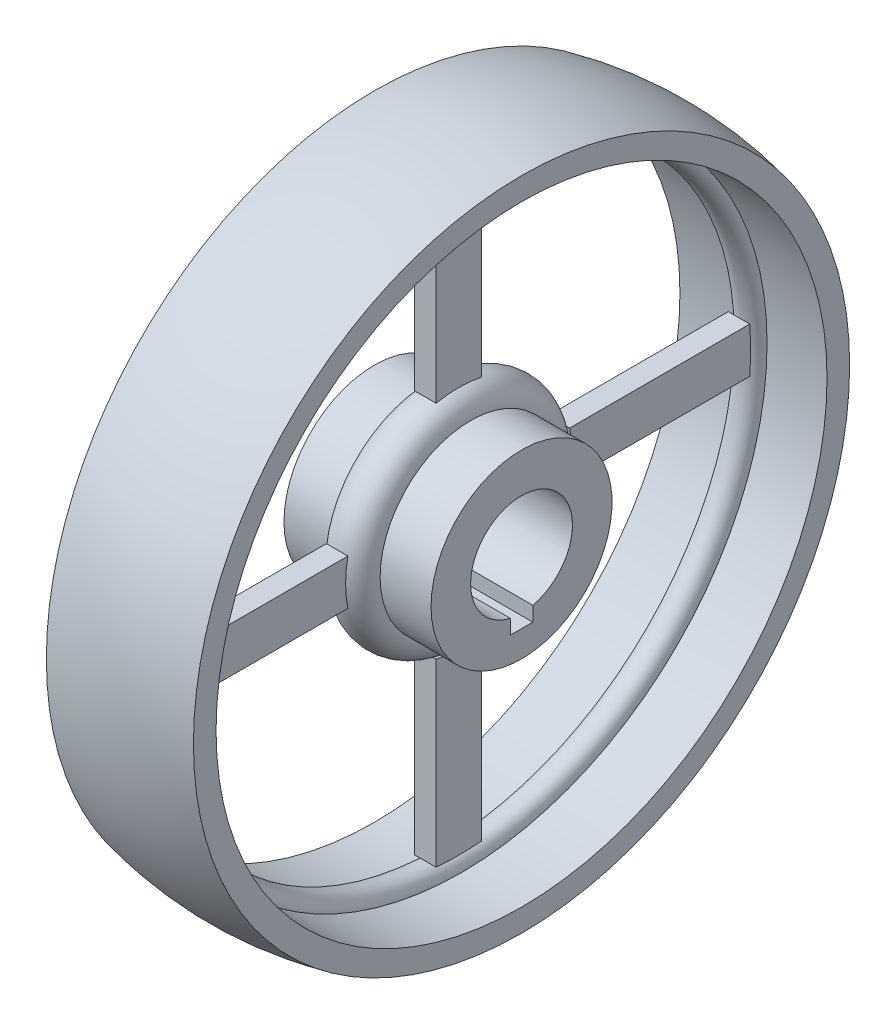
SolidWorks part; units mm, degrees
ref_plane "Front Plane" through (0, 0, 0) normal (0, 0, 1) x (1, 0, 0)
ref_plane "Top Plane" through (0, 0, 0) normal (0, 1, 0) x (1, 0, 0)
ref_plane "Right Plane" through (0, 0, 0) normal (1, 0, 0) x (0, 0, -1)
sketch "Sketch1" plane through (0, 0, 0) normal (0, 0, 1) x (1, 0, 0)
  line L0 (-46.3351, 0) -> (51.8981, 0) construction
  line L1 (-32.5, 10) -> (32.5, 10)
  line L2 (-32.5, 40) -> (-10, 40)
  line L5 (32.5, 10) -> (32.5, 40)
  line L6 (-32.5, 10) -> (-32.5, 40)
  line L7 (-32.5, 135) -> (-6, 135)
  line L8 (6, 135) -> (32.5, 135)
  line L9 (-32.5, 135) -> (-32.5, 145)
  line L11 (-46.3351, 135) -> (51.8981, 135) construction
  line L12 (32.5, 135) -> (32.5, 145)
  line L14 (10, 40) -> (32.5, 40)
  line L17 (-46.3351, 40) -> (51.8981, 40) construction
  line L18 (-46.3351, 10) -> (51.8981, 10) construction
  arc A0 (32.5, 145) -> (-32.5, 145) centre (0, 0) ccw
  arc A1 (-6, 135) -> (6, 135) centre (0, 135) ccw
  arc A2 (10, 40) -> (-10, 40) centre (0, 40) ccw
  point P7 (-46.3351, 50)
  point P8 (51.8981, 50)
  point P10 (0, 145)
  point P11 (32.5, 0)
  point P13 (-32.5, 0)
  dimension "D3" = 148.5976
  dimension "D4" = 6
  dimension "D5" = 10
  dimension "D6" = 32.5
  dimension "D7" = 135
  dimension "D1" = 10
  dimension "D2" = 40
revolve "Revolve1" add sketch "Sketch1" angle 360 about L0
sketch "Sketch2" plane through (0, 0, 0) normal (1, 0, 0) x (0, 0, -1)
  circle A0 centre (0, 0) radius 50
  circle A1 centre (0, 0) radius 129
extrude "Boss-Extrude1" add sketch "Sketch2" along normal mid plane 9.5 separate body
sketch "Sketch3" plane through (4.75, 0, 0) normal (1, 0, 0) x (0, 0, -1)
  line L1 (48.9898, 10) -> (128.6118, 10)
  line L2 (10, 48.9898) -> (10, 128.6118)
  line L4 (-10, 48.9898) -> (-10, 128.6118)
  line L5 (48.9898, -10) -> (128.6118, -10)
  line L6 (10, -48.9898) -> (10, -128.6118)
  line L7 (-10, -48.9898) -> (-10, -128.6118)
  line L8 (-48.9898, -10) -> (-128.6118, -10)
  line L9 (-48.9898, 10) -> (-128.6118, 10)
  arc A3 (-10, 128.6118) -> (-128.6118, 10) centre (0, 0) ccw
  arc A4 (-48.9898, -10) -> (-10, -48.9898) centre (0, 0) ccw
  arc A5 (128.6118, 10) -> (10, 128.6118) centre (0, 0) ccw
  arc A6 (-128.6118, -10) -> (-10, -128.6118) centre (0, 0) ccw
  arc A7 (10, -48.9898) -> (48.9898, -10) centre (0, 0) ccw
  arc A8 (-10, 48.9898) -> (-48.9898, 10) centre (0, 0) ccw
  arc A9 (48.9898, 10) -> (10, 48.9898) centre (0, 0) ccw
  arc A10 (10, -128.6118) -> (128.6118, -10) centre (0, 0) ccw
  point P6 (-10, 0)
  point P7 (-10, 129)
  point P15 (10, 10)
  point P16 (311.8265, 99.3613)
  point P17 (353.4068, 54.2895)
  point P26 (0, 0)
  point P31 (0, 0)
  dimension "D1" = 4
extrude "Cut-Extrude5" cut sketch "Sketch3" against normal blind 138 and the other way blind 160 contours L4 A3 L9 A8 | L1 A5 L2 A9 | L5 A10 L6 A7 | L8 A6 L7 A4
sketch "Sketch6" plane through (32.5, 0, 0) normal (1, 0, 0) x (0, 0, -1)
  circle A0 centre (0, 0) radius 22.5
  dimension "D1" = 45
extrude "Cut-Extrude6" cut sketch "Sketch6" against normal blind 138
sketch "Sketch7" plane through (32.5, 0, 0) normal (1, 0, 0) x (0, 0, -1)
  line L1 (-4.9735, -16.6096) -> (4.9735, -16.6096)
  line L2 (-4.9735, -16.6096) -> (-4.9735, -28.3904)
  line L3 (-4.9735, -28.3904) -> (4.9735, -28.3904)
  line L4 (4.9735, -16.6096) -> (4.9735, -28.3904)
  circle A0 centre (0, 0) radius 22.5 construction
  point P0 (0, -22.5)
  dimension "D1" = 4.9735
  dimension "D2" = 4.9735
  dimension "D3" = 16.6096
  dimension "D4" = 28.3904
extrude "Cut-Extrude7" cut sketch "Sketch7" against normal blind 138
